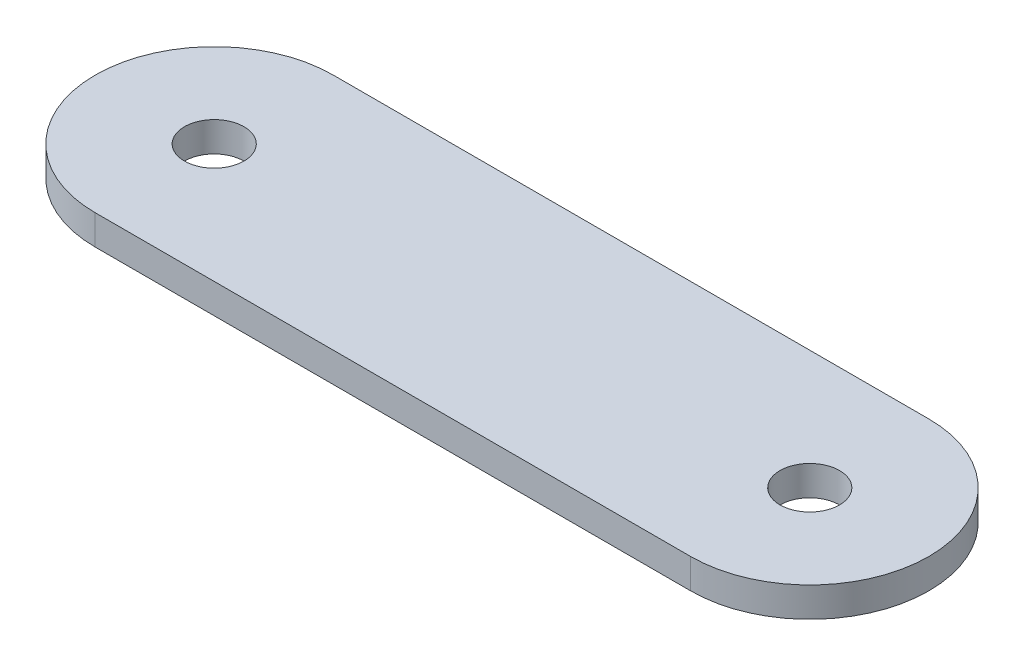
SolidWorks part; units mm, degrees
material "6061-T4 (SS)"
ref_plane "Front Plane" through (0, 0, 0) normal (0, 0, 1) x (1, 0, 0)
ref_plane "Top Plane" through (0, 0, 0) normal (0, 1, 0) x (1, 0, 0)
ref_plane "Right Plane" through (0, 0, 0) normal (1, 0, 0) x (0, 0, -1)
sketch "Sketch1" plane through (0, 0, 0) normal (0, 1, 0) x (1, 0, 0)
  line L0 (15.875, 0) -> (-15.875, 0) construction
  line L1 (15.875, -6.35) -> (-15.875, -6.35)
  line L2 (15.875, 6.35) -> (-15.875, 6.35)
  arc A0 (15.875, -6.35) -> (15.875, 6.35) centre (15.875, 0) ccw
  arc A1 (-15.875, 6.35) -> (-15.875, -6.35) centre (-15.875, 0) ccw
  circle A2 centre (-15.875, 0) radius 1.5875
  circle A3 centre (15.875, 0) radius 1.5875
  point P2 (0, 0)
  point P12 (0, 0)
  point P13 (-22.225, 0)
  point P14 (0, 0)
  point P15 (22.225, 0)
  dimension "D1" = 3.175
  dimension "D3" = 6.35
  dimension "D2" = 6.35
  dimension "D4" = 44.45
  dimension "D5" = 12.7
extrude "Boss-Extrude1" add sketch "Sketch1" along normal blind 1.5875
